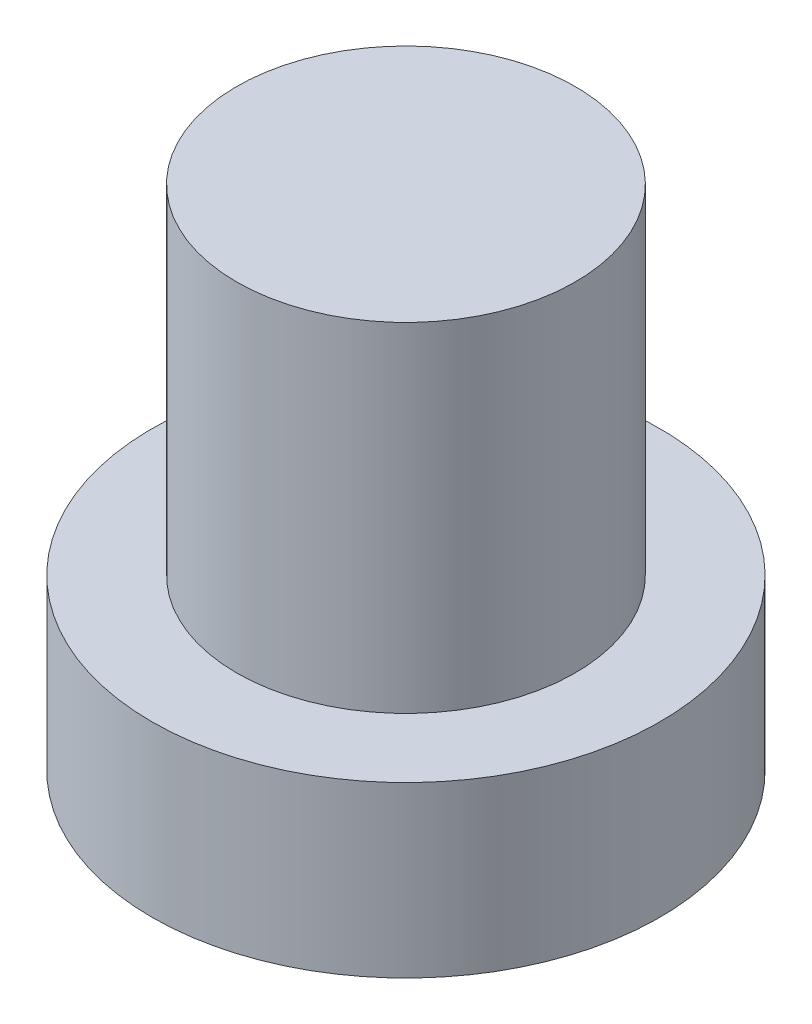
SolidWorks part; units mm, degrees
ref_plane "前视基准面" through (0, 0, 0) normal (0, 0, 1) x (1, 0, 0)
ref_plane "上视基准面" through (0, 0, 0) normal (0, 1, 0) x (1, 0, 0)
ref_plane "右视基准面" through (0, 0, 0) normal (1, 0, 0) x (0, 0, -1)
other "Configuration Table"
sketch "草图1" plane through (0, 0, 0) normal (0, 1, 0) x (1, 0, 0)
  circle A0 centre (0, 0) radius 7.5
  dimension "D1" = 15
extrude "凸台-拉伸1" add sketch "草图1" along normal blind 5
ref_plane "基准面1" through (0, 5, 0) normal (0, 1, 0) x (1, 0, 0)
sketch "草图2" plane through (0, 5, 0) normal (0, 1, 0) x (1, 0, 0)
  circle A0 centre (0, 0) radius 5
  dimension "D1" = 10
extrude "凸台-拉伸2" add sketch "草图2" along normal blind 10
cosmetic thread "装饰螺纹线1" parameters "D2"=9
ref_plane "基准面2" through (0, 0, 0) normal (0, -1, 0) x (-1, 0, 0)
sketch "草图3" plane through (0, 0, 0) normal (0, -1, 0) x (-1, 0, 0)
  line L0 (0, 0) -> (8.3475, 0) construction
  line L1 (0, 0) -> (0, 5.3195) construction
  line L3 (-1.607, 5.5724) -> (1.607, 5.5724)
  line L4 (-1.607, 5.5724) -> (-1.607, -5.5724)
  line L5 (-1.607, -5.5724) -> (1.607, -5.5724)
  line L6 (1.607, 5.5724) -> (1.607, -5.5724)
extrude "切除-拉伸1" cut sketch "草图3" against normal blind 3
